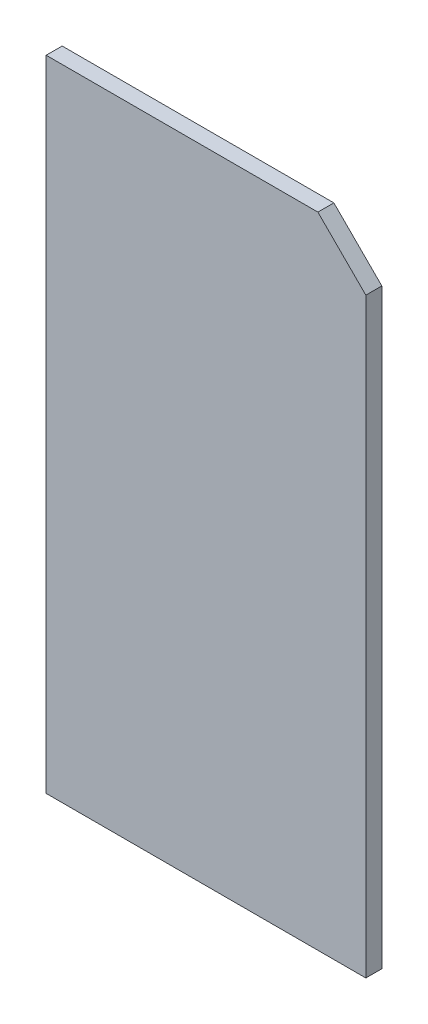
SolidWorks part; units mm, degrees
ref_plane "Front Plane" through (0, 0, 0) normal (0, 0, 1) x (1, 0, 0)
ref_plane "Top Plane" through (0, 0, 0) normal (0, 1, 0) x (1, 0, 0)
ref_plane "Right Plane" through (0, 0, 0) normal (1, 0, 0) x (0, 0, -1)
sketch "Sketch3" plane through (0, 0, 0) normal (0, 0, 1) x (1, 0, 0)
  line L0 (250, 500) -> (250, -500)
  line L1 (-250, -500) -> (250, -500)
  line L2 (-250, -500) -> (-250, 500)
  line L3 (-250, 500) -> (250, 500)
  dimension "D1" = 500
  dimension "plate_width" = 1000
  dimension "D2" = 250
  dimension "D3" = 500
extrude "Boss-Extrude2" add sketch "Sketch3" along normal blind 25
sketch "Sketch4" plane through (0, 0, 25) normal (0, 0, 1) x (1, 0, 0)
  line L0 (175, 500) -> (250, 425)
  line L1 (250, 500) -> (-250, 500) construction
  line L2 (250, -500) -> (250, 500) construction
  line L3 (250, 425) -> (250, 500)
  line L4 (250, 500) -> (175, 500)
  dimension "D1" = 75
  dimension "D2" = 75
extrude "Cut-Extrude1" cut sketch "Sketch4" against normal blind 25.4
equation "\"D1@Sketch3\"=\"plate_width@Sketch3\"/2"
equation "\"D3@Sketch3\"=\"plate_width@Sketch3\"/2"
equation "\"D2@Sketch3\"=\"plate_width@Sketch3\"/4"
